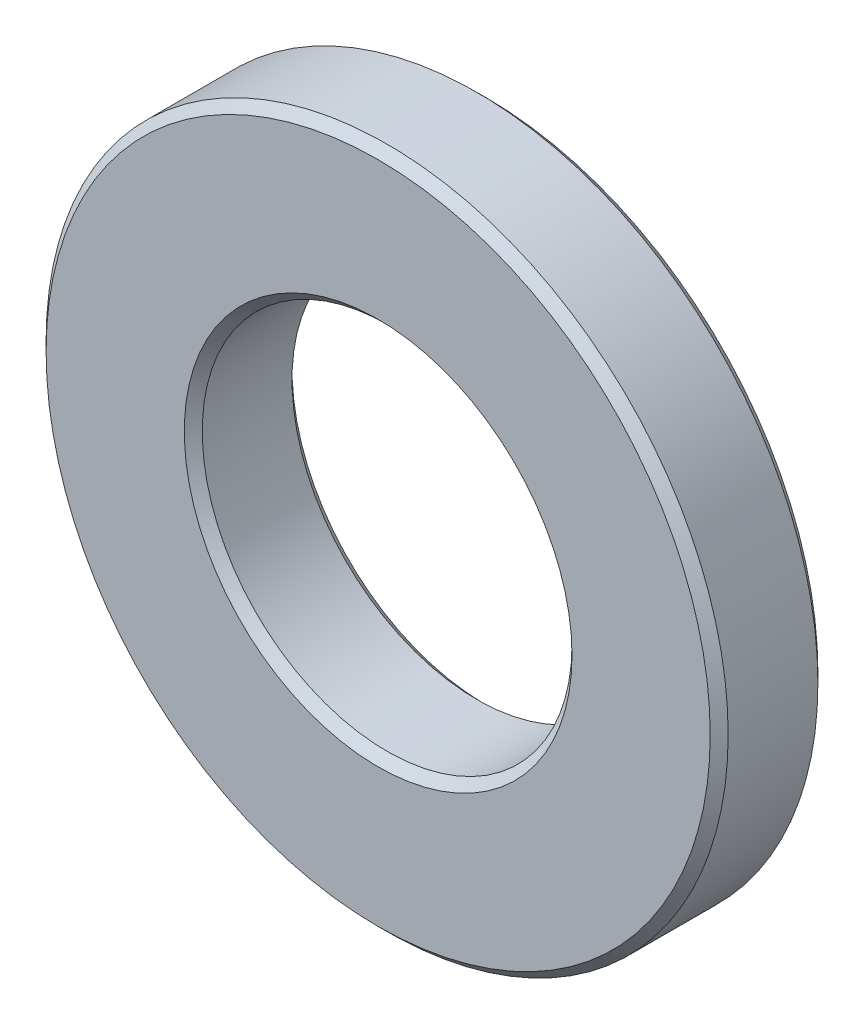
SolidWorks part; units mm, degrees
material "4340 H/T-Y"
ref_plane "Front Plane" through (0, 0, 0) normal (0, 0, 1) x (1, 0, 0)
ref_plane "Top Plane" through (0, 0, 0) normal (0, 1, 0) x (1, 0, 0)
ref_plane "Right Plane" through (0, 0, 0) normal (1, 0, 0) x (0, 0, -1)
sketch "Sketch1" plane through (0, 0, 0) normal (0, 0, 1) x (1, 0, 0)
  circle A0 centre (0, 0) radius 10.3
  circle A1 centre (0, 0) radius 19
  dimension "D1" = 38
  dimension "D2" = 20.6
extrude "Extrude1" add sketch "Sketch1" along normal blind 6
chamfer "Chamfer1" distance 0.5 angle 45 4 edges at (19, 0, 0) (19, 0, 6) (10.3, 0, 0) (10.3, 0, 6)
